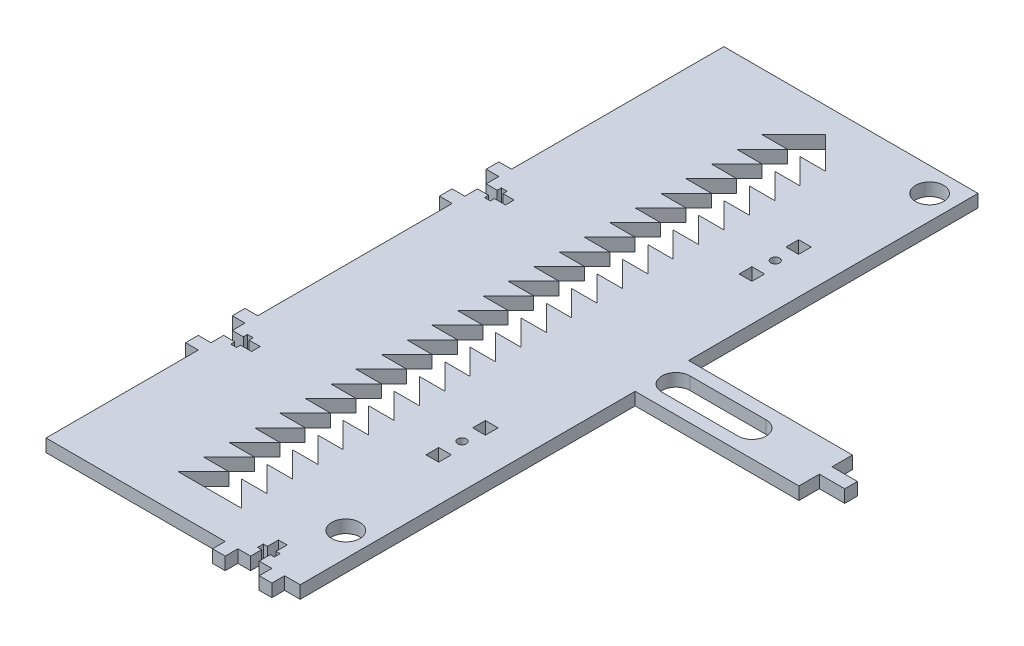
SolidWorks part; units mm, degrees
ref_plane "Front Plane" through (0, 0, 0) normal (0, 0, 1) x (1, 0, 0)
ref_plane "Top Plane" through (0, 0, 0) normal (0, 1, 0) x (1, 0, 0)
ref_plane "Right Plane" through (0, 0, 0) normal (1, 0, 0) x (0, 0, -1)
sketch "Axle Support Plate" plane through (0, 0, 0) normal (0, 1, 0) x (1, 0, 0)
  line L0 (51.4759, 157.4574) -> (51.4759, -134.6426) construction
  line L1 (38.7759, 169.5676) -> (38.7759, -103.4054) construction
  line L2 (0, 156.8676) -> (-15.875, 140.9926)
  line L3 (-15.875, 140.9926) -> (-3.175, 140.9926)
  line L4 (63.5861, -169.5676) -> (63.5861, -1.9727)
  line L5 (-63.5861, 169.5676) -> (63.5861, -169.5676) construction
  line L6 (-63.5861, -169.5676) -> (63.5861, 169.5676) construction
  line L7 (-63.5861, -63.6496) -> (-63.5861, 33.6324)
  line L8 (-63.5861, 169.5676) -> (63.5861, 169.5676)
  line L9 (0, 169.5676) -> (0, -169.5676) construction
  line L10 (15.875, 140.9926) -> (0, 156.8676)
  line L11 (-3.175, 140.9926) -> (-15.875, 128.2926)
  line L12 (-15.875, 128.2926) -> (-3.175, 128.2926)
  line L13 (15.875, 128.2926) -> (3.175, 140.9926)
  line L14 (-3.175, 128.2926) -> (-15.875, 115.5926)
  line L15 (-15.875, 115.5926) -> (-3.175, 115.5926)
  line L16 (15.875, 115.5926) -> (3.175, 128.2926)
  line L17 (63.5861, 11.4074) -> (4.2777, 11.4074) construction
  line L18 (-3.175, 115.5926) -> (-15.875, 102.8926)
  line L19 (-15.875, 102.8926) -> (-3.175, 102.8926)
  line L20 (15.875, 102.8926) -> (3.175, 115.5926)
  line L21 (-3.175, 102.8926) -> (-15.875, 90.1926)
  line L22 (-15.875, 90.1926) -> (-3.175, 90.1926)
  line L23 (55.7939, -169.5676) -> (63.5861, -169.5676)
  line L24 (15.875, 90.1926) -> (3.175, 102.8926)
  line L25 (-3.175, 90.1926) -> (-15.875, 77.4926)
  line L26 (-15.875, 77.4926) -> (-3.175, 77.4926)
  line L27 (15.875, 77.4926) -> (3.175, 90.1926)
  line L28 (-3.175, 77.4926) -> (-15.875, 64.7926)
  line L29 (-15.875, 64.7926) -> (-3.175, 64.7926)
  line L30 (15.875, 64.7926) -> (3.175, 77.4926)
  line L31 (-3.175, 64.7926) -> (-15.875, 52.0926)
  line L32 (-15.875, 52.0926) -> (-3.175, 52.0926)
  line L33 (15.875, 52.0926) -> (3.175, 64.7926)
  line L34 (-3.175, 52.0926) -> (-15.875, 39.3926)
  line L35 (-15.875, 39.3926) -> (-3.175, 39.3926)
  line L36 (15.875, 39.3926) -> (3.175, 52.0926)
  line L37 (63.5861, 24.7876) -> (145.5462, 24.7876)
  line L38 (145.5462, 24.7876) -> (145.5462, 14.5824)
  line L39 (145.5462, -1.9727) -> (63.5861, -1.9727)
  line L40 (70.6162, 11.4074) -> (108.7162, 11.4074) construction
  line L41 (70.6162, 18.4376) -> (108.7162, 18.4376)
  line L42 (70.6162, 4.3773) -> (108.7162, 4.3773)
  line L43 (145.5462, 8.2324) -> (158.2462, 8.2324)
  line L44 (158.2462, 8.2324) -> (158.2462, 14.5824)
  line L45 (158.2462, 14.5824) -> (145.5462, 14.5824)
  line L46 (63.5861, 24.7876) -> (63.5861, 169.5676)
  line L47 (63.5861, 24.7876) -> (63.5861, -1.9727) construction
  line L48 (63.5861, 11.4074) -> (158.2462, 11.4074) construction
  line L49 (-3.175, 39.3926) -> (-15.875, 26.6926)
  line L50 (-15.875, 26.6926) -> (-3.175, 26.6926)
  line L51 (145.5462, 8.2324) -> (145.5462, -1.9727)
  line L52 (15.875, 26.6926) -> (3.175, 39.3926)
  line L53 (-3.175, 26.6926) -> (-15.875, 13.9926)
  line L54 (-15.875, 13.9926) -> (-3.175, 13.9926)
  line L55 (15.875, 13.9926) -> (3.175, 26.6926)
  line L56 (-3.175, 13.9926) -> (-15.875, 1.2926)
  line L57 (-15.875, 1.2926) -> (-3.175, 1.2926)
  line L58 (15.875, 1.2926) -> (3.175, 13.9926)
  line L59 (3.175, -11.4074) -> (15.875, -11.4074)
  line L60 (-15.875, -11.4074) -> (-3.175, -11.4074)
  line L61 (15.875, -11.4074) -> (3.175, 1.2926)
  line L62 (-3.175, -11.4074) -> (-15.875, -24.1074)
  line L63 (-15.875, -24.1074) -> (-3.175, -24.1074)
  line L64 (15.875, -24.1074) -> (3.175, -11.4074)
  line L65 (-3.175, -24.1074) -> (-15.875, -36.8074)
  line L66 (-15.875, -36.8074) -> (-3.175, -36.8074)
  line L67 (15.875, -36.8074) -> (3.175, -24.1074)
  line L68 (-3.175, -36.8074) -> (-15.875, -49.5074)
  line L69 (-15.875, -49.5074) -> (-3.175, -49.5074)
  line L70 (15.875, -49.5074) -> (3.175, -36.8074)
  line L71 (-3.175, -49.5074) -> (-15.875, -62.2074)
  line L72 (-15.875, -62.2074) -> (-3.175, -62.2074)
  line L73 (15.875, -62.2074) -> (3.175, -49.5074)
  line L74 (-3.175, -62.2074) -> (-15.875, -74.9074)
  line L75 (-15.875, -74.9074) -> (-3.175, -74.9074)
  line L76 (15.875, -74.9074) -> (3.175, -62.2074)
  line L77 (-3.175, -74.9074) -> (-15.875, -87.6074)
  line L78 (-15.875, -87.6074) -> (-3.175, -87.6074)
  line L79 (15.875, -87.6074) -> (3.175, -74.9074)
  line L80 (-3.175, -87.6074) -> (-15.875, -100.3074)
  line L81 (-63.5861, 63.3504) -> (-63.5861, 169.5676)
  line L82 (-15.875, -100.3074) -> (-3.175, -100.3074)
  line L83 (15.875, -100.3074) -> (3.175, -87.6074)
  line L84 (-3.175, -100.3074) -> (-15.875, -113.0074)
  line L85 (-15.875, -113.0074) -> (-3.175, -113.0074)
  line L86 (15.875, -113.0074) -> (3.175, -100.3074)
  line L87 (-3.175, -113.0074) -> (-15.875, -125.7074)
  line L88 (-15.875, -125.7074) -> (-3.175, -125.7074)
  line L89 (15.875, -125.7074) -> (3.175, -113.0074)
  line L90 (26.0759, -169.5676) -> (-63.5861, -169.5676)
  line L91 (-3.175, -125.7074) -> (-15.875, -138.4074)
  line L92 (-15.875, -138.4074) -> (-3.175, -138.4074)
  line L93 (15.875, -138.4074) -> (3.175, -125.7074)
  line L94 (-63.5861, -169.5676) -> (-63.5861, -93.3676)
  line L95 (-3.175, -138.4074) -> (-15.875, -151.1074)
  line L96 (-15.875, -151.1074) -> (15.875, -151.1074)
  line L97 (15.875, -151.1074) -> (3.175, -138.4074)
  line L98 (3.175, 140.9926) -> (15.875, 140.9926)
  line L99 (3.175, 115.5926) -> (15.875, 115.5926)
  line L100 (3.175, 128.2926) -> (15.875, 128.2926)
  line L101 (3.175, 102.8926) -> (15.875, 102.8926)
  line L102 (3.175, 77.4926) -> (15.875, 77.4926)
  line L103 (3.175, 90.1926) -> (15.875, 90.1926)
  line L104 (3.175, 64.7926) -> (15.875, 64.7926)
  line L105 (3.175, 52.0926) -> (15.875, 52.0926)
  line L106 (3.175, 39.3926) -> (15.875, 39.3926)
  line L107 (3.175, 26.6926) -> (15.875, 26.6926)
  line L108 (3.175, 13.9926) -> (15.875, 13.9926)
  line L109 (3.175, 1.2926) -> (15.875, 1.2926)
  line L110 (-3.175, 1.2926) -> (-15.875, -11.4074)
  line L111 (0, 4.4676) -> (-1.2184, 3.2492) [skipped]
  line L112 (3.175, -24.1074) -> (15.875, -24.1074)
  line L113 (3.175, -36.8074) -> (15.875, -36.8074)
  line L114 (3.175, -49.5074) -> (15.875, -49.5074)
  line L115 (3.175, -62.2074) -> (15.875, -62.2074)
  line L116 (3.175, -74.9074) -> (15.875, -74.9074)
  line L117 (3.175, -87.6074) -> (15.875, -87.6074)
  line L118 (3.175, -100.3074) -> (15.875, -100.3074)
  line L119 (3.175, -113.0074) -> (15.875, -113.0074)
  line L120 (3.175, -125.7074) -> (15.875, -125.7074)
  line L121 (3.175, -138.4074) -> (15.875, -138.4074)
  circle A0 centre (51.4759, 157.4574) radius 7.0301
  circle A1 centre (51.4759, -134.6426) radius 7.0301
  arc A4 (70.6162, 18.4376) -> (70.6162, 4.3773) centre (70.6162, 11.4074) ccw
  arc A5 (108.7162, 4.3773) -> (108.7162, 18.4376) centre (108.7162, 11.4074) ccw
  point P8 (0, 0)
  point P15 (51.4759, 11.4074)
  point P57 (89.6662, 11.4074)
  line B0 (-63.5861, -69.9996) -> (-69.9361, -69.9996)
  line B1 (-69.9361, -69.9996) -> (-69.9361, -63.6496)
  line B2 (-69.9361, -63.6496) -> (-63.5861, -63.6496)
  line B3 (-63.5861, -76.3496) -> (-58.0511, -76.3496)
  line B4 (-58.0511, -76.3496) -> (-58.0511, -74.3086)
  line B5 (-58.0511, -74.3086) -> (-55.1511, -74.3086)
  line B6 (-55.1511, -74.3086) -> (-55.1511, -76.3496)
  line B7 (-55.1511, -76.3496) -> (-49.6161, -76.3496)
  line B8 (-49.6161, -76.3496) -> (-49.6161, -80.6676)
  line B9 (-49.6161, -80.6676) -> (-55.1511, -80.6676)
  line B10 (-55.1511, -80.6676) -> (-55.1511, -82.7086)
  line B11 (-55.1511, -82.7086) -> (-58.0511, -82.7086)
  line B12 (-58.0511, -82.7086) -> (-58.0511, -80.6676)
  line B13 (-58.0511, -80.6676) -> (-63.5861, -80.6676)
  line B14 (-49.6161, -78.5086) -> (-63.5861, -78.5086) construction
  line B15 (-63.5861, -87.0176) -> (-63.5861, -80.6676)
  line B16 (-69.9361, -93.3676) -> (-63.5861, -93.3676)
  line B17 (-63.5861, -69.9996) -> (-63.5861, -76.3496)
  line B18 (-69.9361, -87.0176) -> (-69.9361, -93.3676)
  line B19 (-63.5861, -87.0176) -> (-69.9361, -87.0176)
  line B20 (-63.5861, 57.0004) -> (-69.9361, 57.0004)
  line B21 (-69.9361, 57.0004) -> (-69.9361, 63.3504)
  line B22 (-69.9361, 63.3504) -> (-63.5861, 63.3504)
  line B23 (-63.5861, 50.6504) -> (-58.0511, 50.6504)
  line B24 (-58.0511, 50.6504) -> (-58.0511, 52.6914)
  line B25 (-58.0511, 52.6914) -> (-55.1511, 52.6914)
  line B26 (-55.1511, 52.6914) -> (-55.1511, 50.6504)
  line B27 (-55.1511, 50.6504) -> (-49.6161, 50.6504)
  line B28 (-49.6161, 50.6504) -> (-49.6161, 46.3324)
  line B29 (-49.6161, 46.3324) -> (-55.1511, 46.3324)
  line B30 (-55.1511, 46.3324) -> (-55.1511, 44.2914)
  line B31 (-55.1511, 44.2914) -> (-58.0511, 44.2914)
  line B32 (-58.0511, 44.2914) -> (-58.0511, 46.3324)
  line B33 (-58.0511, 46.3324) -> (-63.5861, 46.3324)
  line B34 (-49.6161, 48.4914) -> (-63.5861, 48.4914) construction
  line B35 (-63.5861, 39.9824) -> (-63.5861, 46.3324)
  line B36 (-69.9361, 33.6324) -> (-63.5861, 33.6324)
  line B37 (-63.5861, 57.0004) -> (-63.5861, 50.6504)
  line B38 (-69.9361, 39.9824) -> (-69.9361, 33.6324)
  line B39 (-63.5861, 39.9824) -> (-69.9361, 39.9824)
  line B40 (32.4259, -169.5676) -> (32.4259, -175.9176)
  line B41 (32.4259, -175.9176) -> (26.0759, -175.9176)
  line B42 (26.0759, -175.9176) -> (26.0759, -169.5676)
  line B43 (38.7759, -169.5676) -> (38.7759, -164.0326)
  line B44 (38.7759, -164.0326) -> (36.7349, -164.0326)
  line B45 (36.7349, -164.0326) -> (36.7349, -161.1326)
  line B46 (36.7349, -161.1326) -> (38.7759, -161.1326)
  line B47 (38.7759, -161.1326) -> (38.7759, -155.5976)
  line B48 (38.7759, -155.5976) -> (43.0939, -155.5976)
  line B49 (43.0939, -155.5976) -> (43.0939, -161.1326)
  line B50 (43.0939, -161.1326) -> (45.1349, -161.1326)
  line B51 (45.1349, -161.1326) -> (45.1349, -164.0326)
  line B52 (45.1349, -164.0326) -> (43.0939, -164.0326)
  line B53 (43.0939, -164.0326) -> (43.0939, -169.5676)
  line B54 (40.9349, -155.5976) -> (40.9349, -169.5676) construction
  line B55 (49.4439, -169.5676) -> (43.0939, -169.5676)
  line B56 (55.7939, -175.9176) -> (55.7939, -169.5676)
  line B57 (32.4259, -169.5676) -> (38.7759, -169.5676)
  line B58 (49.4439, -175.9176) -> (55.7939, -175.9176)
  line B59 (49.4439, -169.5676) -> (49.4439, -175.9176)
  line B60 (41.9509, 74.9074) -> (41.9509, 104.6254) construction
  line B61 (39.7919, 89.7664) -> (44.1099, 89.7664) construction
  line B62 (38.7759, 98.2754) -> (45.1259, 98.2754)
  line B63 (38.7759, 98.2754) -> (38.7759, 104.6254)
  line B64 (38.7759, 104.6254) -> (45.1259, 104.6254)
  line B65 (45.1259, 98.2754) -> (45.1259, 104.6254)
  line B66 (38.7759, 98.2754) -> (45.1259, 104.6254) construction
  line B67 (38.7759, 104.6254) -> (45.1259, 98.2754) construction
  line B68 (38.7759, 74.9074) -> (45.1259, 81.2574) construction
  line B69 (38.7759, 81.2574) -> (45.1259, 74.9074) construction
  line B70 (45.1259, 81.2574) -> (45.1259, 74.9074)
  line B71 (38.7759, 74.9074) -> (45.1259, 74.9074)
  line B72 (38.7759, 81.2574) -> (38.7759, 74.9074)
  line B73 (38.7759, 81.2574) -> (45.1259, 81.2574)
  circle B74 centre (41.9509, 89.7664) radius 2.159
  line B75 (41.9509, -52.0926) -> (41.9509, -81.8106) construction
  line B76 (39.7919, -66.9516) -> (44.1099, -66.9516) construction
  line B77 (38.7759, -75.4606) -> (45.1259, -75.4606)
  line B78 (38.7759, -75.4606) -> (38.7759, -81.8106)
  line B79 (38.7759, -81.8106) -> (45.1259, -81.8106)
  line B80 (45.1259, -75.4606) -> (45.1259, -81.8106)
  line B81 (38.7759, -75.4606) -> (45.1259, -81.8106) construction
  line B82 (38.7759, -81.8106) -> (45.1259, -75.4606) construction
  line B83 (38.7759, -52.0926) -> (45.1259, -58.4426) construction
  line B84 (38.7759, -58.4426) -> (45.1259, -52.0926) construction
  line B85 (45.1259, -58.4426) -> (45.1259, -52.0926)
  line B86 (38.7759, -52.0926) -> (45.1259, -52.0926)
  line B87 (38.7759, -58.4426) -> (38.7759, -52.0926)
  line B88 (38.7759, -58.4426) -> (45.1259, -58.4426)
  circle B89 centre (41.9509, -66.9516) radius 2.159
  dimension "D1" = 5.08
  dimension "D4" = 14.0603
  dimension "D5" = 5.08
  dimension "D8" = 31.75
  dimension "D14" = 14.0603
  dimension "D22" = 7.0301
  dimension "D25" = 36.83
  dimension "D2" = 292.1
  dimension "D6" = 12.7
  dimension "D7" = 63.5
  dimension "D9" = 89.662
  dimension "D10" = 12.7
  dimension "D11" = 24
  dimension "D12" = 10.541
  dimension "D13" = 34.925
  dimension "D23" = 6.35
  dimension "D24" = 38.1
  dimension "D26" = 12.7
  dimension "D27" = 6.35
  dimension "D29" = 76.2
  dimension "D30" = 203.2
sketch_block_instance "Male T-slot assembly-1"
sketch_block "Male T-slot assembly" parameters "D1"=6.35, "D2"=6.35, "D3"=4.318, "D4"=2.9, "D5"=8.4, "D6"=13.97, "D7"=6.35
sketch_block_instance "Male T-slot assembly-2"
sketch_block_instance "Male T-slot assembly-4"
sketch_block_instance "Female T-Slot Assembly-1"
sketch_block "Female T-Slot Assembly" parameters "D4"=4.318, "D1"=6.35, "D2"=6.35, "D3"=6.35
sketch_block_instance "Female T-Slot Assembly-3"
extrude "Boss-Extrude1" add sketch "Axle Support Plate" along normal blind 6.35
equation "\"Ball Diameter\"= 1.75in"
equation "\"Sheet Thickness\"= 0.25in"
equation "\"Screw Diameter\"= .17in"
equation "\"Robot Diameter\"= 14in"
equation "\"Castor Screw Diameter\"= 0.22in"
equation "\"Wheel Diameter\"= 4in"
equation "\"Nut Diameter\"= 8.4mm"
equation "\"Nut Height\"= 2.9mm"
equation "\"Screw Height\"= 0.55in"
equation "\"Pulley Diameter\"= 1in"
equation "\"Reactor Height\"= 14in"
equation "\"Elevator Height\"= 11.5in"
equation "\"Elevator Width\"= \"Ball Diameter\" + 0.25in"
equation "\"D1@Boss-Extrude1\"=\"Sheet Thickness\""
equation "\"Elevator Bearing Diameter\"= sqr(2*(\"Sheet Thickness\"^2)) + 0.2in"
equation "\"Elevator Axle Length\"= \"Elevator Width\" + 8*\"Sheet Thickness\""
equation "\"D4@Axle Support Plate\"=\"Elevator Bearing Diameter\""
equation "\"D6@Axle Support Plate\"=(\"Pulley Diameter\")/2"
equation "\"D13@Axle Support Plate\"=2.5in - \"Sheet Thickness\" - (\"Ball Diameter\")/2"
equation "\"D9@Axle Support Plate\"=\"Elevator Clearance from Axis\" + \"Sheet Thickness\""
equation "\"D14@Axle Support Plate\" = \"Elevator Bearing Diameter\""
equation "\"D22@Axle Support Plate\"=\"Elevator Bearing Diameter\"/2"
equation "\"D23@Axle Support Plate\" = \"Sheet Thickness\""
equation "\"Elevator Axle Endcap Diameter\"= \"Pulley Diameter\" + 0.25in"
equation "\"D25@Axle Support Plate\"=\"Elevator Axle Endcap Diameter\"+0.2in"
equation "\"D27@Axle Support Plate\"=\"Sheet Thickness\""
equation "\"Elevator Clearance from Axis\"= 3.28in"
